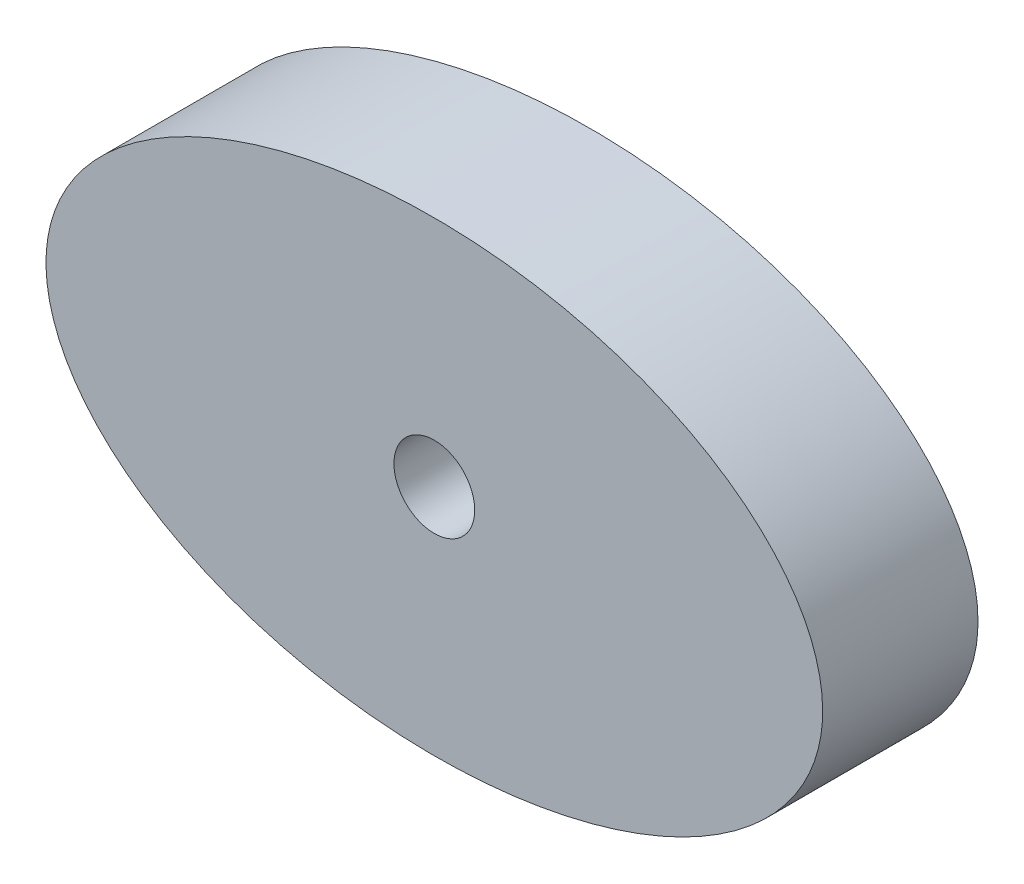
SolidWorks part; units mm, degrees
ref_plane "Alzado" through (0, 0, 0) normal (0, 0, 1) x (1, 0, 0)
ref_plane "Planta" through (0, 0, 0) normal (0, 1, 0) x (1, 0, 0)
ref_plane "Vista lateral" through (0, 0, 0) normal (1, 0, 0) x (0, 0, -1)
sketch "Croquis2" plane through (0, 0, 0) normal (0, 0, 1) x (1, 0, 0)
  circle A0 centre (0, 0) radius 2.6
  ellipse E0 centre (0, 0) end of major axis (25, 0) minor radius 15
  dimension "D3" = 5.2
  dimension "D1" = 30
  dimension "D2" = 50
extrude "Saliente-Extruir1" add sketch "Croquis2" along normal mid plane 10
